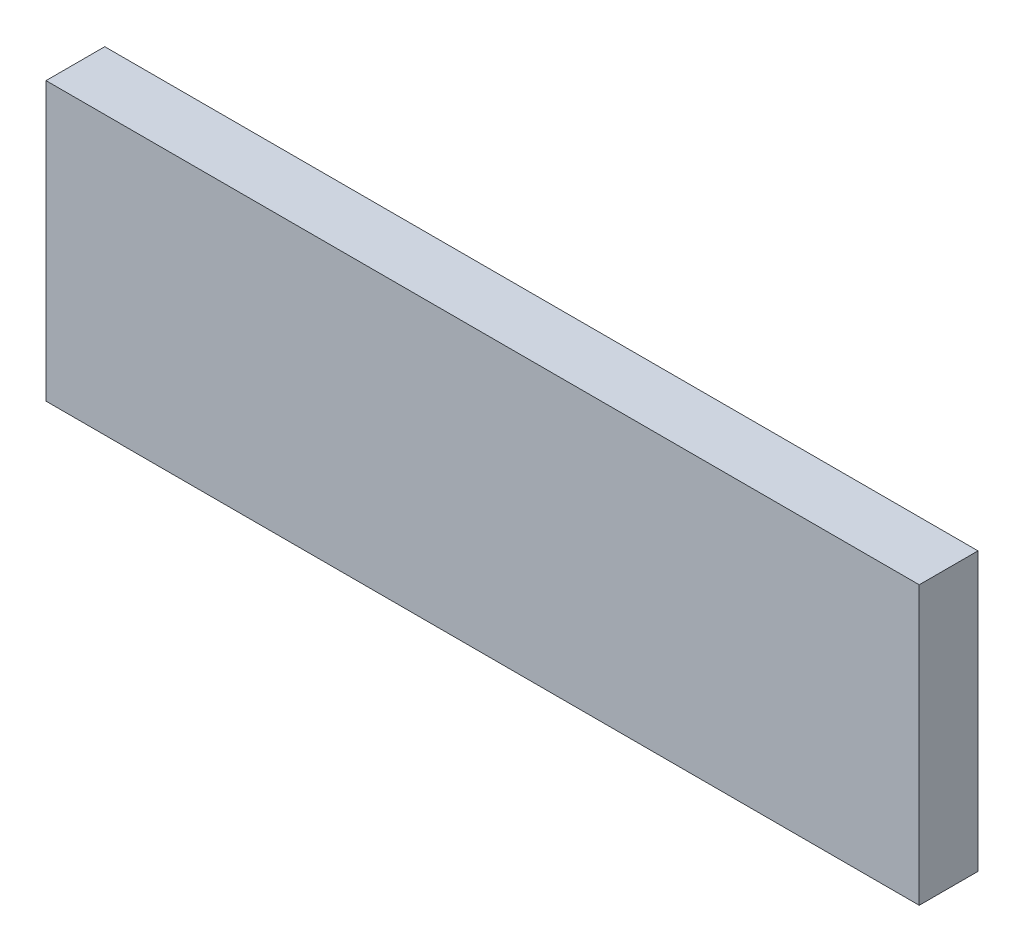
SolidWorks part; units mm, degrees
ref_plane "Front Plane" through (0, 0, 0) normal (0, 0, 1) x (1, 0, 0)
ref_plane "Top Plane" through (0, 0, 0) normal (0, 1, 0) x (1, 0, 0)
ref_plane "Right Plane" through (0, 0, 0) normal (1, 0, 0) x (0, 0, -1)
sketch "Sketch1" plane through (0, 0, 0) normal (0, 0, 1) x (1, 0, 0)
  line L1 (-141.55, 90) -> (141.55, 90)
  line L2 (-141.55, 90) -> (-141.55, 0)
  line L3 (-141.55, 0) -> (141.55, 0)
  line L4 (141.55, 90) -> (141.55, 0)
  dimension "D1" = 90
  dimension "D2" = 283.1
extrude "Boss-Extrude1" add sketch "Sketch1" along normal blind 19.05
